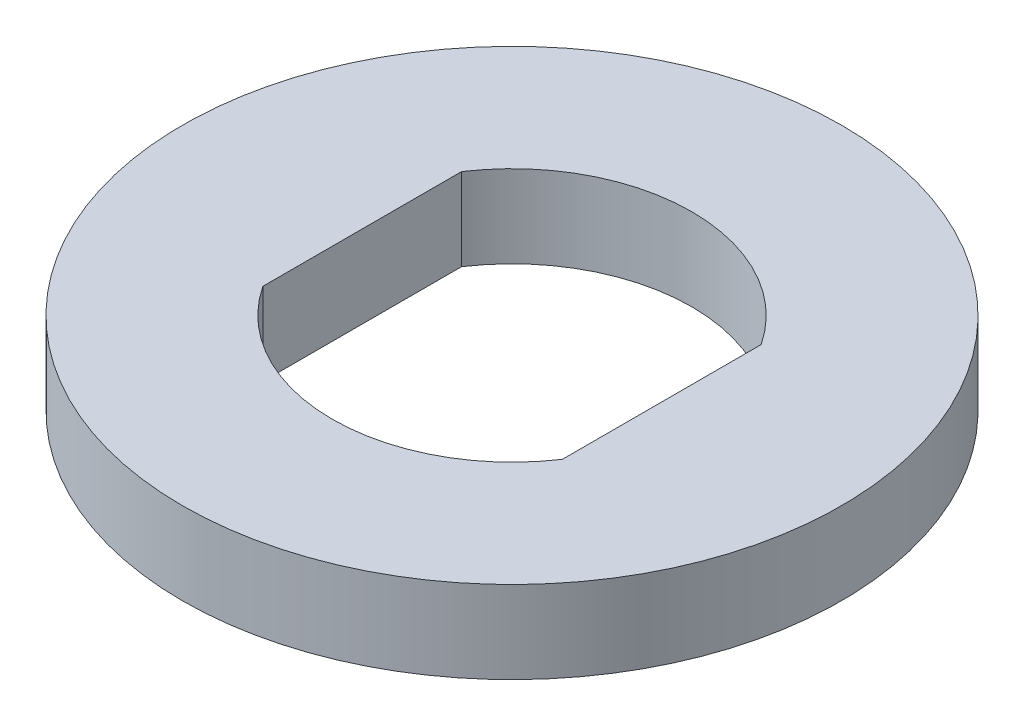
SolidWorks part; units mm, degrees
material "AISI 1045 Steel, cold drawn"
ref_plane "Front Plane" through (0, 0, 0) normal (0, 0, 1) x (1, 0, 0)
ref_plane "Top Plane" through (0, 0, 0) normal (0, 1, 0) x (1, 0, 0)
ref_plane "Right Plane" through (0, 0, 0) normal (1, 0, 0) x (0, 0, -1)
sketch "Sketch1" plane through (0, 0, 0) normal (0, 1, 0) x (1, 0, 0)
  line L0 (-5, 3.3166) -> (-5, -3.3166)
  line L1 (-5, -3.3166) -> (5, -3.3166) construction
  line L2 (5, -3.3166) -> (5, 3.3166)
  circle A0 centre (0, 0) radius 11
  arc A1 (5, 3.3166) -> (-5, 3.3166) centre (0, 0) ccw
  arc A2 (-5, -3.3166) -> (5, -3.3166) centre (0, 0) ccw
  dimension "D1" = 22
  dimension "D3" = 6
  dimension "D2" = 10
extrude "Boss-Extrude1" add sketch "Sketch1" along normal mid plane 2.75
